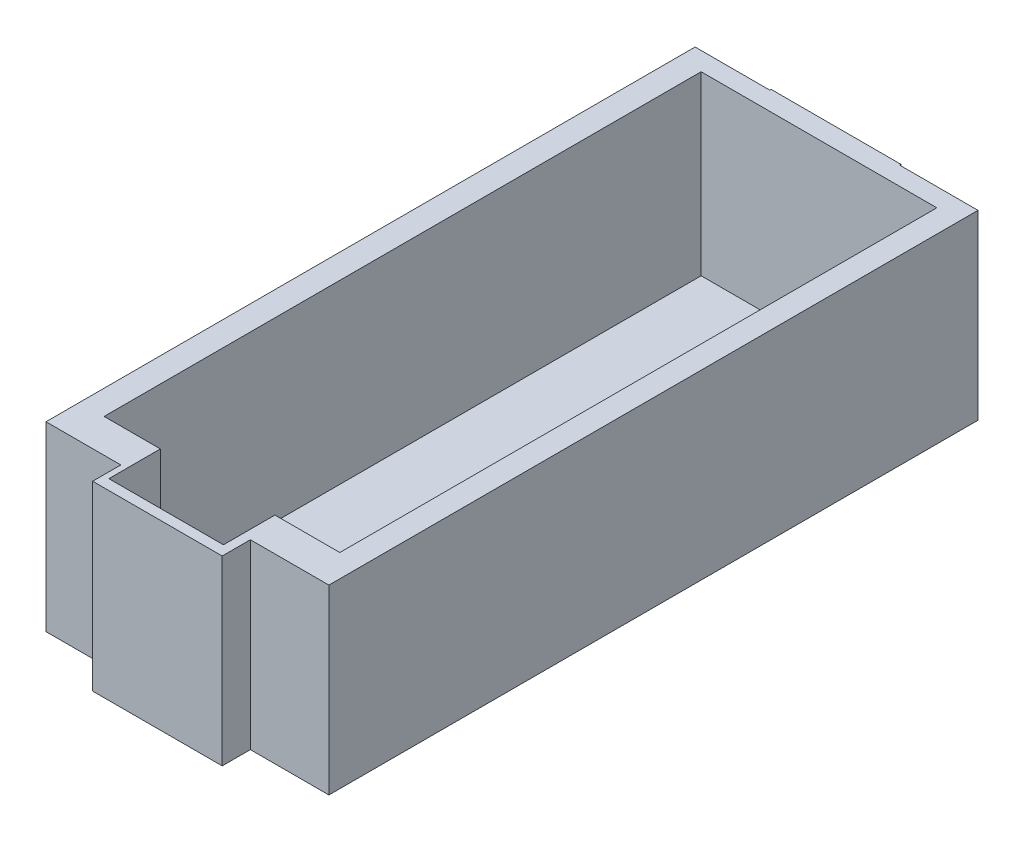
SolidWorks part; units mm, degrees
ref_plane "Front Plane" through (0, 0, 0) normal (0, 0, 1) x (1, 0, 0)
ref_plane "Top Plane" through (0, 0, 0) normal (0, 1, 0) x (1, 0, 0)
ref_plane "Right Plane" through (0, 0, 0) normal (1, 0, 0) x (0, 0, -1)
sketch3d "3DSketch1"
  line L1 (-4.1027, 20.3641, 0.0572) -> (-4.1027, 12.5387, 0.0572)
  line L2 (-4.1027, 20.3641, 0.0572) -> (8.0752, 20.3641, 0.0572)
  line L3 (8.0752, 20.3641, 0.0572) -> (8.0752, 12.5387, 0.0572)
  line L4 (-4.1027, 12.5387, 0.0572) -> (8.0752, 12.5387, 0.0572)
  dimension "D1" = 7.8254
  dimension "D2" = 12.178
extrude "Boss-Extrude1" add sketch "3DSketch1" along direction (0, 0, 1) on the side against the normal blind 27.94
sketch "Sketch2" plane through (0, 0, 0) normal (0, 0, 1) x (1, 0, 0)
  line L0 (-4.1027, 20.3641) -> (8.0752, 20.3641) construction
  line L1 (-0.8824, 20.3641) -> (4.6941, 20.3641)
  line L2 (-0.8824, 20.3641) -> (-0.8824, 12.5387)
  line L3 (-0.8824, 12.5387) -> (4.6941, 12.5387)
  line L4 (4.6941, 20.3641) -> (4.6941, 12.5387)
  line L5 (-4.1027, 12.5387) -> (8.0752, 12.5387) construction
extrude "Boss-Extrude4" add sketch "Sketch2" along normal blind 29.21
sketch "Sketch4" plane through (8.0752, 0, 0) normal (1, 0, 0) x (0, 0, -1)
sketch "Sketch8" plane through (0, 20.3641, 0) normal (0, 1, 0) x (1, 0, 0)
  line L1 (-3.0504, -26.5483) -> (7.0959, -26.5483)
  line L2 (-3.0504, -26.5483) -> (-3.0504, -0.8492)
  line L3 (-3.0504, -0.8492) -> (7.0959, -0.8492)
  line L4 (7.0959, -26.5483) -> (7.0959, -0.8492)
  line L5 (-3.0504, -26.5483) -> (7.0959, -0.8492) construction
  line L6 (-3.0504, -0.8492) -> (7.0959, -26.5483) construction
  point P0 (2.0227, -13.6988)
  dimension "D1" = 10.1463
  dimension "D2" = 10.1463
  dimension "D3" = 25.6991
  dimension "D4" = 10.1463
extrude "Cut-Extrude2" cut sketch "Sketch8" against normal blind 7.6063
sketch "Sketch10" plane through (0, 20.3641, 0) normal (0, 1, 0) x (1, 0, 0)
  line L0 (-3.0504, -26.5483) -> (7.0959, -26.5483) construction
  line L1 (-0.6284, -28.7652) -> (4.3035, -28.7652)
  line L2 (-0.6284, -28.7652) -> (-0.6284, -26.5483)
  line L3 (-0.6284, -26.5483) -> (4.3035, -26.5483)
  line L4 (4.3035, -28.7652) -> (4.3035, -26.5483)
  line L5 (-0.6284, -28.7652) -> (4.3035, -26.5483) construction
  line L6 (-0.6284, -26.5483) -> (4.3035, -28.7652) construction
  point P0 (1.8376, -27.6568)
extrude "Cut-Extrude3" cut sketch "Sketch10" against normal blind 7.6063
